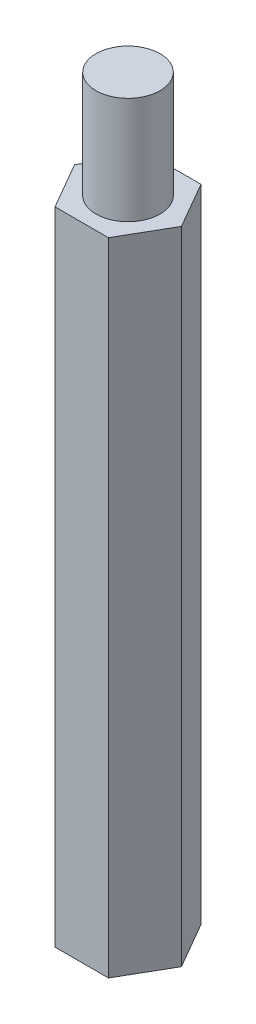
SolidWorks part; units mm, degrees
material "2.0402 (CuZn40Pb2)"
ref_plane "Front" through (0, 0, 0) normal (0, 0, 1) x (1, 0, 0)
ref_plane "Top" through (0, 0, 0) normal (0, 1, 0) x (1, 0, 0)
ref_plane "Right" through (0, 0, 0) normal (1, 0, 0) x (0, 0, -1)
sketch "Эскиз1" plane through (0, 0, 0) normal (0, 1, 0) x (1, 0, 0)
  line L1 (1.25, -2.1651) -> (2.5, 0)
  line L2 (2.5, 0) -> (1.25, 2.1651)
  line L3 (1.25, 2.1651) -> (-1.25, 2.1651)
  line L4 (-1.25, 2.1651) -> (-2.5, 0)
  line L5 (-2.5, 0) -> (-1.25, -2.1651)
  line L6 (-1.25, -2.1651) -> (1.25, -2.1651)
  circle A0 centre (0, 0) radius 2.1651 construction
  circle A1 centre (0, 0) radius 2.5 construction
  dimension "D1" = 5
  dimension "D2" = 2.5
extrude "Бобышка-Вытянуть1" add sketch "Эскиз1" along normal blind 30
sketch "Эскиз2" plane through (0, 30, 0) normal (0, 1, 0) x (1, 0, 0)
  circle A0 centre (0, 0) radius 1.5
  dimension "D1" = 3
extrude "Бобышка-Вытянуть2" add sketch "Эскиз2" along normal blind 5
sketch "Эскиз3" plane through (0, 0, 0) normal (0, -1, 0) x (1, 0, 0)
  circle A0 centre (0, 0) radius 1.5
  dimension "D1" = 3
extrude "Вырез-Вытянуть1" cut sketch "Эскиз3" against normal blind 10
